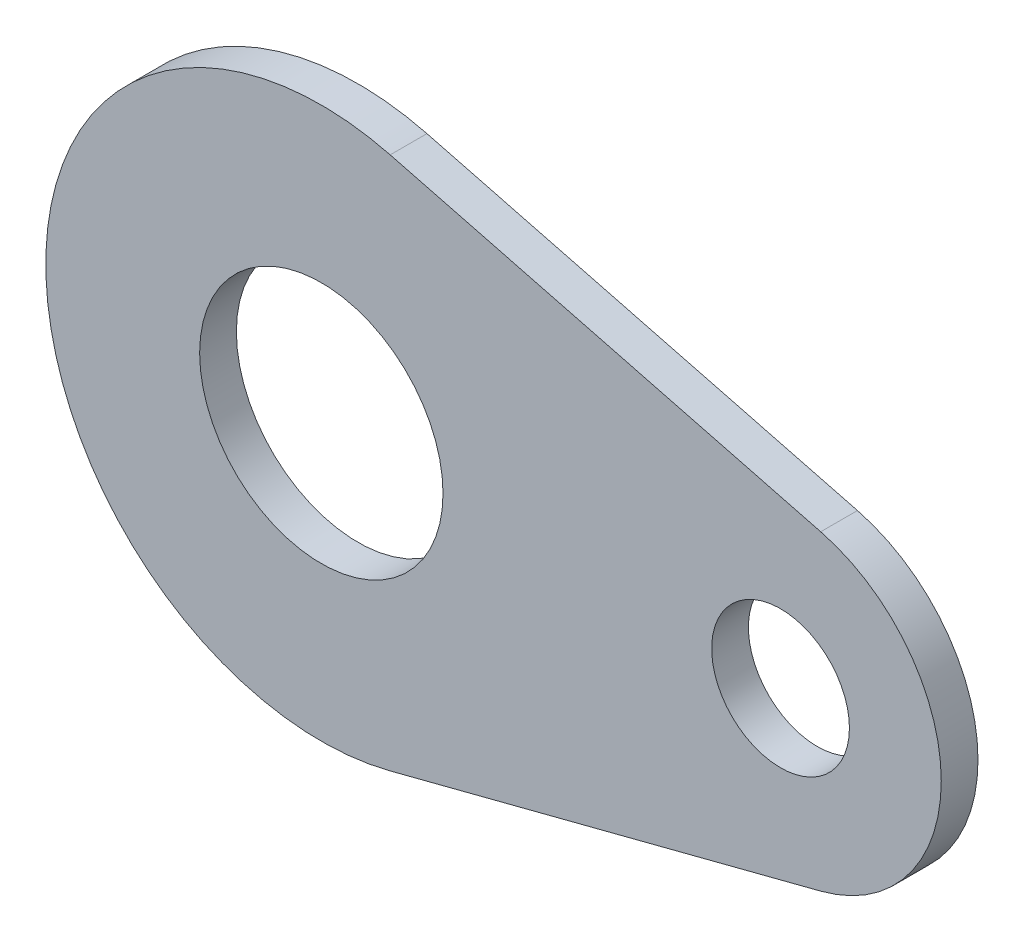
SolidWorks part; units mm, degrees
material "AISI 316 Stainless Steel Sheet (SS)"
ref_plane "Front" through (0, 0, 0) normal (0, 0, 1) x (1, 0, 0)
ref_plane "Top" through (0, 0, 0) normal (0, 1, 0) x (1, 0, 0)
ref_plane "Right" through (0, 0, 0) normal (1, 0, 0) x (0, 0, -1)
sketch "Sketch1" plane through (0, 0, 0) normal (0, 0, 1) x (1, 0, 0)
  line L0 (0, 0) -> (10, 0) construction
  line L1 (1.5, 5.8095) -> (10.875, 3.3889)
  line L2 (10.875, -3.3889) -> (1.5, -5.8095)
  circle A0 centre (0, 0) radius 2.65
  circle A1 centre (0, 0) radius 6 construction
  circle A2 centre (10, 0) radius 1.5
  circle A3 centre (10, 0) radius 3.5 construction
  arc A4 (10.875, 3.3889) -> (10.875, -3.3889) centre (10, 0) cw
  arc A5 (1.5, 5.8095) -> (1.5, -5.8095) centre (0, 0) ccw
  point P13 (0, 0)
  point P14 (0, 0)
  dimension "D1" = 5.3
  dimension "D2" = 12
  dimension "D3" = 3
  dimension "D4" = 7
  dimension "D5" = 10
extrude "Boss-Extrude1" add sketch "Sketch1" along normal blind 0.8
